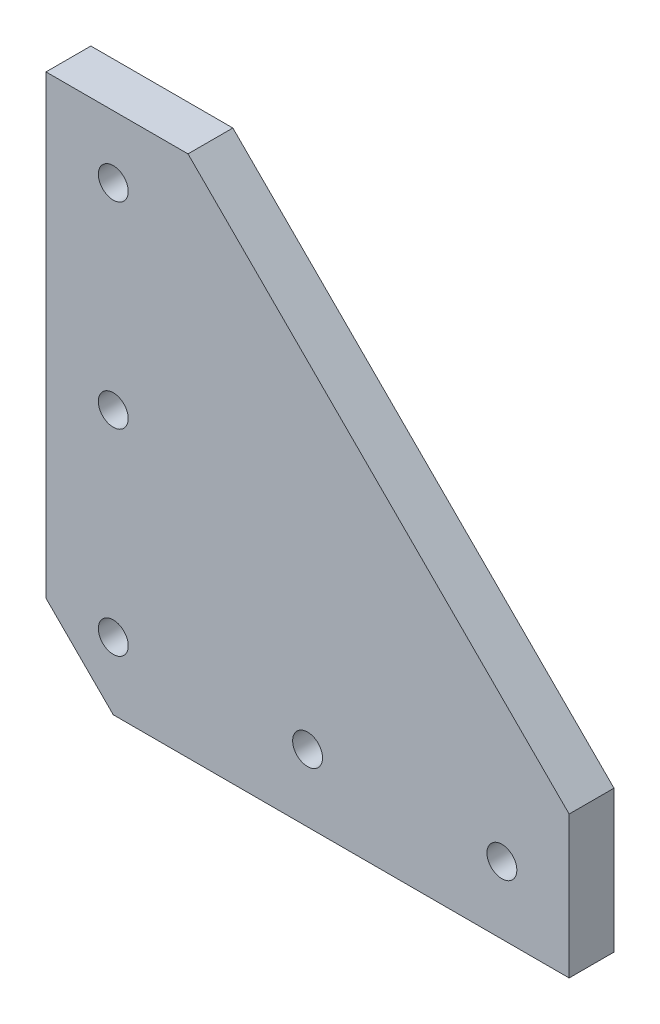
SolidWorks part; units mm, degrees
ref_plane "Front Plane" through (0, 0, 0) normal (0, 0, 1) x (1, 0, 0)
ref_plane "Top Plane" through (0, 0, 0) normal (0, 1, 0) x (1, 0, 0)
ref_plane "Right Plane" through (0, 0, 0) normal (1, 0, 0) x (0, 0, -1)
sketch "Sketch1" plane through (0, 0, 0) normal (0, 0, 1) x (1, 0, 0)
  line L0 (0, 70) -> (0, 0)
  line L1 (0, 0) -> (70, 0)
  line L2 (70, 0) -> (70, 19)
  line L3 (70, 19) -> (19, 70)
  line L4 (19, 70) -> (0, 70)
  line L5 (9, 35.3219) -> (9, 61.6438) construction
  line L6 (9, 35.3219) -> (9, 9) construction
  line L7 (9, 9) -> (35, 9) construction
  line L8 (35, 9) -> (61, 9) construction
  circle A0 centre (9, 9) radius 2
  circle A1 centre (35, 9) radius 2
  circle A2 centre (61, 9) radius 2
  circle A3 centre (9, 61.6438) radius 2
  circle A4 centre (9, 35.3219) radius 2
  dimension "D8" = 4
  dimension "D1" = 19
  dimension "D2" = 19
  dimension "D3" = 45
  dimension "D4" = 70
  dimension "D5" = 9
  dimension "D6" = 9
  dimension "D7" = 9
  dimension "D9" = 52.6438
extrude "Boss-Extrude1" add sketch "Sketch1" along normal blind 6
chamfer "Chamfer1" distance 9 angle 45 1 edges at (0, 0, 3)
